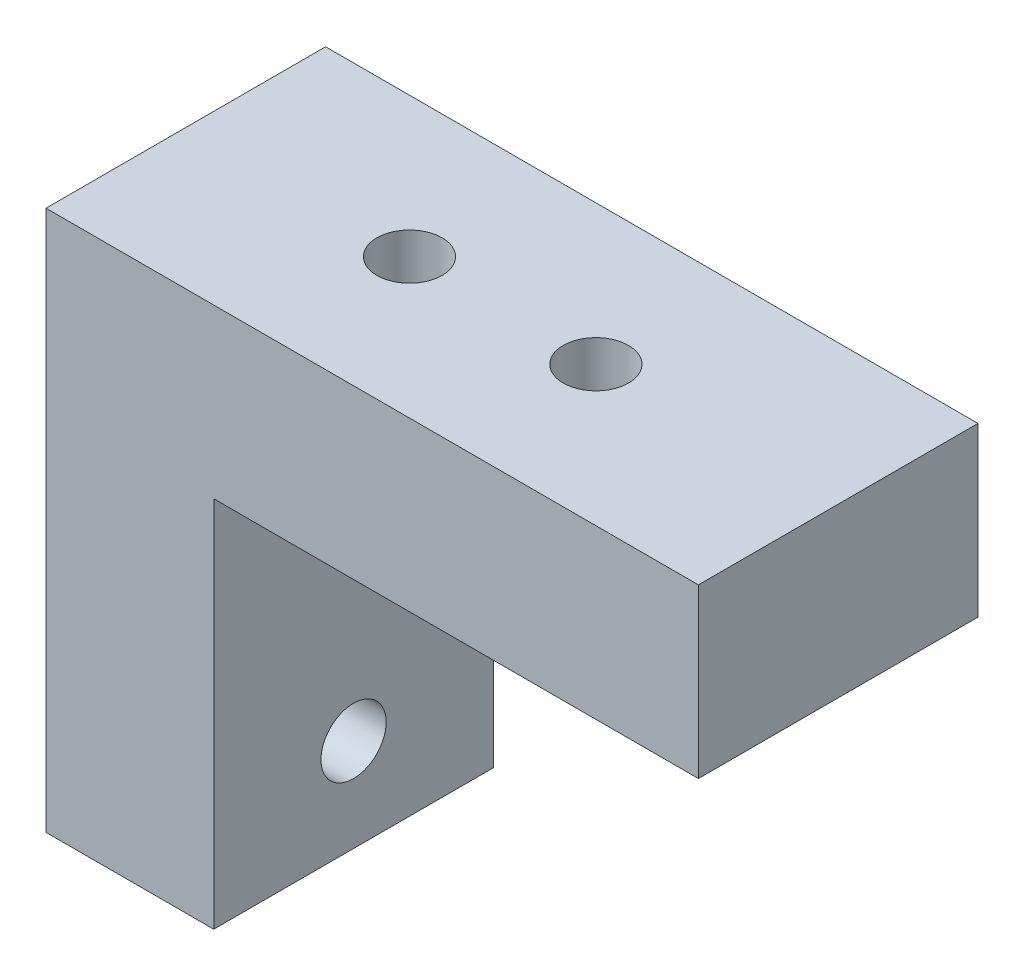
SolidWorks part; units mm, degrees
ref_plane "Front Plane" through (0, 0, 0) normal (0, 0, 1) x (1, 0, 0)
ref_plane "Top Plane" through (0, 0, 0) normal (0, 1, 0) x (1, 0, 0)
ref_plane "Right Plane" through (0, 0, 0) normal (1, 0, 0) x (0, 0, -1)
sketch "Sketch2" plane through (0, 0, 0) normal (1, 0, 0) x (0, 0, -1)
  line L1 (-4.6476, -10.7047) -> (10.3524, -10.7047)
  line L2 (-4.6476, -10.7047) -> (-4.6476, 9.2953)
  line L3 (-4.6476, 9.2953) -> (10.3524, 9.2953)
  line L4 (10.3524, -10.7047) -> (10.3524, 9.2953)
  dimension "D1" = 20
  dimension "D2" = 15
extrude "Boss-Extrude1" add sketch "Sketch2" along normal blind 9
sketch "Sketch3" plane through (9, 0, 0) normal (1, 0, 0) x (0, 0, -1)
  line L0 (2.8524, -5.7047) -> (2.8524, 4.2953) construction
  line L1 (2.8524, 4.2953) -> (2.8524, 9.2953) construction
  line L2 (10.3524, 9.2953) -> (-4.6476, 9.2953) construction
  circle A0 centre (2.8524, -5.7047) radius 1.75
  circle A1 centre (2.8524, 4.2953) radius 1.75
  dimension "D1" = 3.5
  dimension "D2" = 10
  dimension "D3" = 5
extrude "Cut-Extrude1" cut sketch "Sketch3" against normal through all
sketch "Sketch4" plane through (0, 9.2953, 0) normal (0, 1, 0) x (1, 0, 0)
  line L0 (9, 10.3524) -> (0, 10.3524) construction
  line L1 (0, -4.6476) -> (35, -4.6476)
  line L2 (0, -4.6476) -> (0, 10.3524)
  line L3 (0, 10.3524) -> (35, 10.3524)
  line L4 (35, -4.6476) -> (35, 10.3524)
  dimension "D1" = 35
extrude "Boss-Extrude2" add sketch "Sketch4" along normal blind 9
sketch "Sketch5" plane through (0, 18.2953, 0) normal (0, 1, 0) x (1, 0, 0)
  line L0 (12, 2.8524) -> (22, 2.8524) construction
  line L1 (22, 2.8524) -> (35, 2.8524) construction
  line L2 (35, -4.6476) -> (35, 10.3524) construction
  circle A0 centre (12, 2.8524) radius 1.75
  circle A1 centre (22, 2.8524) radius 1.75
  dimension "D1" = 3.5
  dimension "D2" = 10
  dimension "D3" = 3
extrude "Cut-Extrude2" cut sketch "Sketch5" against normal through all
